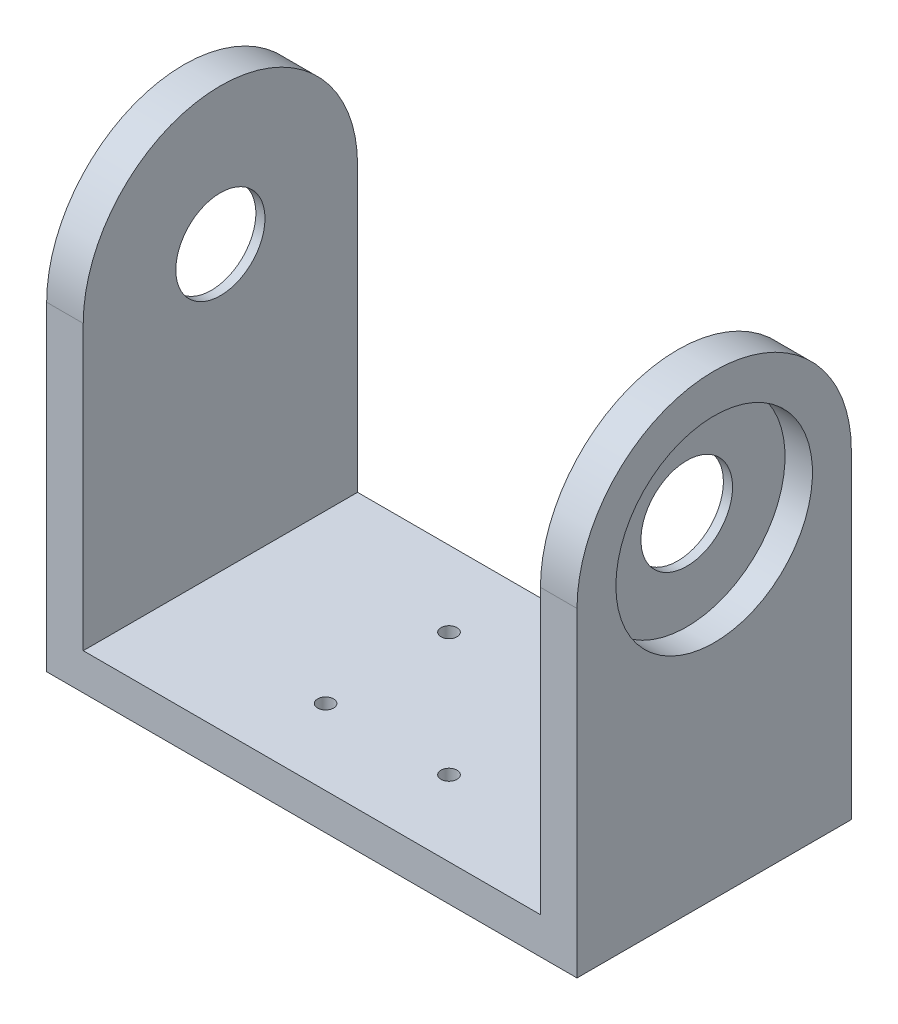
SolidWorks part; units mm, degrees
ref_plane "Front Plane" through (0, 0, 0) normal (0, 0, 1) x (1, 0, 0)
ref_plane "Top Plane" through (0, 0, 0) normal (0, 1, 0) x (1, 0, 0)
ref_plane "Right Plane" through (0, 0, 0) normal (1, 0, 0) x (0, 0, -1)
sketch "Sketch2" plane through (0, 0, 0) normal (0, 1, 0) x (1, 0, 0)
  line L1 (-25, 15) -> (25, 15)
  line L2 (-25, 15) -> (-25, -15)
  line L3 (-25, -15) -> (25, -15)
  line L4 (25, 15) -> (25, -15)
  line L5 (-25, 15) -> (25, -15) construction
  line L6 (-25, -15) -> (25, 15) construction
  point P0 (0, 0)
  dimension "D1" = 50
  dimension "D2" = 30
extrude "Boss-Extrude1" add sketch "Sketch2" along normal blind 4
sketch "Sketch3" plane through (-25, 0, 0) normal (-1, 0, 0) x (0, 0, 1)
  line L0 (-15, 0) -> (-15, 35)
  line L1 (15, 35) -> (15, 0)
  line L2 (-15, 0) -> (15, 0)
  arc A0 (-15, 35) -> (15, 35) centre (0, 35) cw
  circle A1 centre (0, 35) radius 10.75
  dimension "D1" = 21.5
  dimension "D2" = 35
extrude "Boss-Extrude2" add sketch "Sketch3" along normal blind 4
mirror "Mirror1" about plane through (0, 0, 0) normal (1, 0, 0) of "Boss-Extrude2"
sketch "Sketch4" plane through (-25, 0, 0) normal (1, 0, 0) x (0, 0, -1)
  circle A0 centre (0, 35) radius 6.25
  circle A1 centre (0, 35) radius 10.75 construction
  circle A2 centre (0, 35) radius 10.75
  dimension "D1" = 4.5
  dimension "D2" = 21.5
extrude "Boss-Extrude3" add sketch "Sketch4" against normal blind 1
mirror "Mirror2" about plane through (0, 0, 0) normal (1, 0, 0) of "Boss-Extrude3"
sketch "Sketch5" plane through (26, 0, 0) normal (1, 0, 0) x (0, 0, -1)
  circle A0 centre (0, 35) radius 6.25 construction
  circle A1 centre (0, 35) radius 6.25
  circle A2 centre (0, 35) radius 5.01
  dimension "D1" = 1.24
extrude "Boss-Extrude4" add sketch "Sketch5" against normal up to surface (1 mm away) up to face at (25, 23.25, 0)
sketch "Sketch6" plane through (-26, 0, 0) normal (-1, 0, 0) x (0, 0, 1)
  circle A0 centre (0, 35) radius 4.875
  circle A1 centre (0, 35) radius 6.25 construction
  circle A2 centre (0, 35) radius 6.25
  dimension "D1" = 9.75
  dimension "D2" = 1.375
extrude "Boss-Extrude5" add sketch "Sketch6" against normal up to surface (1 mm away) up to face at (-25, 23.25, 0)
sketch "Sketch7" plane through (-26, 0, 0) normal (-1, 0, 0) x (0, 0, 1)
  circle A0 centre (0, 35) radius 4.9438
  dimension "D1" = 9.8876
sketch "Sketch8" plane through (0, 0, 0) normal (0, -1, 0) x (1, 0, 0)
  line L1 (-6.75, 6.75) -> (6.75, 6.75) construction
  line L2 (-6.75, 6.75) -> (-6.75, -6.75) construction
  line L3 (-6.75, -6.75) -> (6.75, -6.75) construction
  line L4 (6.75, 6.75) -> (6.75, -6.75) construction
  line L5 (-6.75, 6.75) -> (6.75, -6.75) construction
  line L6 (-6.75, -6.75) -> (6.75, 6.75) construction
  circle A0 centre (-6.75, 6.75) radius 0.875
  circle A1 centre (6.75, 6.75) radius 0.875
  circle A2 centre (6.75, -6.75) radius 0.875
  circle A3 centre (-6.75, -6.75) radius 0.875
  point P1 (0, 0)
  point P16 (0, 0)
  dimension "D2" = 1.75
  dimension "D1" = 13.5
  dimension "D3" = 4
extrude "Cut-Extrude1" cut sketch "Sketch8" against normal blind 10
